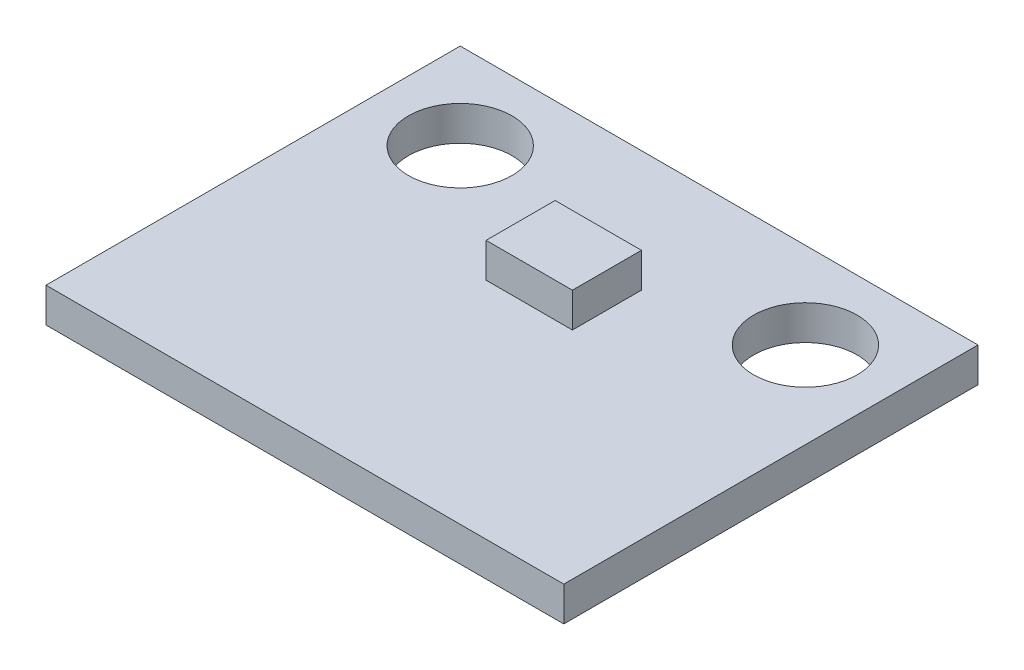
SolidWorks part; units mm, degrees
ref_plane "Front Plane" through (0, 0, 0) normal (0, 0, 1) x (1, 0, 0)
ref_plane "Top Plane" through (0, 0, 0) normal (0, 1, 0) x (1, 0, 0)
ref_plane "Right Plane" through (0, 0, 0) normal (1, 0, 0) x (0, 0, -1)
sketch "Sketch1" plane through (0, 0, 0) normal (0, 1, 0) x (1, 0, 0)
  line L1 (-7.5, 6) -> (7.5, 6)
  line L2 (-7.5, 6) -> (-7.5, -6)
  line L3 (-7.5, -6) -> (7.5, -6)
  line L4 (7.5, 6) -> (7.5, -6)
  line L5 (-7.5, 6) -> (7.5, -6) construction
  line L6 (-7.5, -6) -> (7.5, 6) construction
  circle A0 centre (-5, 3.5) radius 1.5
  circle A1 centre (5, 3.5) radius 1.5
  point P0 (0, 0)
  dimension "D3" = 3
  dimension "D1" = 15
  dimension "D2" = 12
  dimension "D4" = 2.5
  dimension "D5" = 2.5
  dimension "D6" = 2.5
extrude "PCB" add sketch "Sketch1" along normal blind 1
sketch "Sketch2" plane through (0, 1, 0) normal (0, 1, 0) x (1, 0, 0)
  line L1 (-1.25, 2.5) -> (1.25, 2.5)
  line L2 (-1.25, 2.5) -> (-1.25, 0.5)
  line L3 (-1.25, 0.5) -> (1.25, 0.5)
  line L4 (1.25, 2.5) -> (1.25, 0.5)
  line L5 (-1.25, 2.5) -> (1.25, 0.5) construction
  line L6 (-1.25, 0.5) -> (1.25, 2.5) construction
  circle A0 centre (5, 3.5) radius 1.5 construction
  point P0 (0, 1.5)
  dimension "D1" = 2
  dimension "D2" = 2.5
  dimension "D3" = 2
extrude "Sensor" add sketch "Sketch2" along normal blind 1
